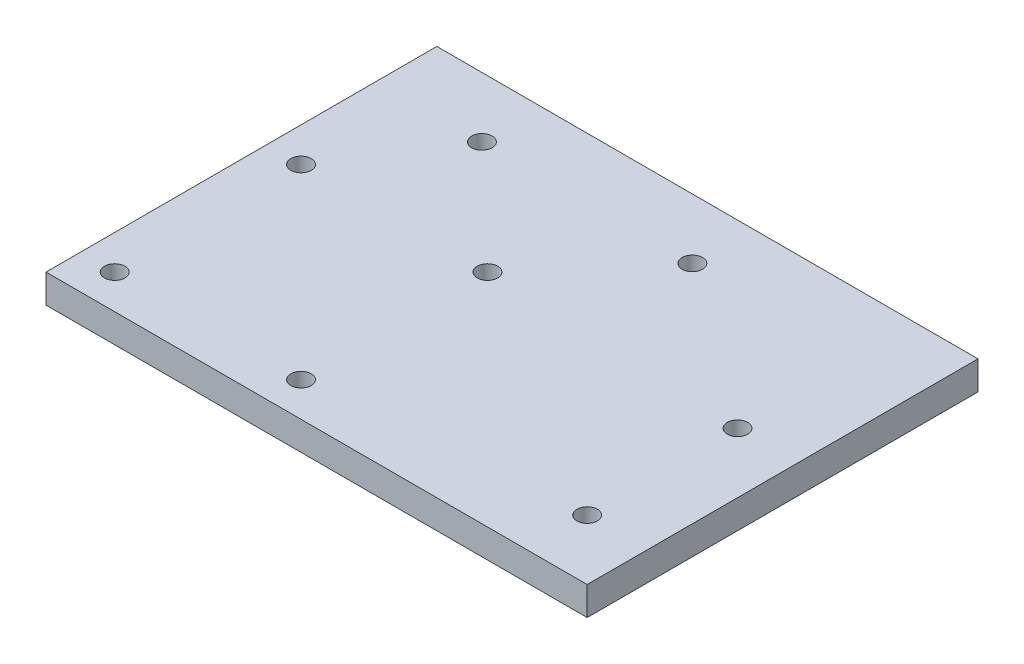
SolidWorks part; units mm, degrees
material "6061 Alloy"
ref_plane "Front Plane" through (0, 0, 0) normal (0, 0, 1) x (1, 0, 0)
ref_plane "Top Plane" through (0, 0, 0) normal (0, 1, 0) x (1, 0, 0)
ref_plane "Right Plane" through (0, 0, 0) normal (1, 0, 0) x (0, 0, -1)
sketch "Sketch1" plane through (0, 0, 0) normal (0, 1, 0) x (1, 0, 0)
  line L1 (0, 0) -> (90, 0)
  line L2 (0, 0) -> (0, 65)
  line L3 (0, 65) -> (90, 65)
  line L4 (90, 0) -> (90, 65)
  dimension "D1" = 90
  dimension "D2" = 65
extrude "Boss-Extrude1" add sketch "Sketch1" along normal blind 4.7625
sketch "Sketch3" plane through (0, 0, 0) normal (0, -1, 0) x (1, 0, 0)
  line L9 (35, -55) -> (35, -65) construction
  line L10 (90, -22.5) -> (80, -22.5) construction
  line L11 (80, -55) -> (0, -55) construction
  line L14 (80, 0) -> (80, -55) construction
  point P46 (52.5, -55)
  point P47 (17.5, -55)
  point P48 (80, -35)
  point P49 (80, -10)
  point P50 (36.709, -5.709)
  point P51 (36.709, -36.709)
  point P52 (5.709, -5.709)
  point P53 (5.709, -36.709)
hole_wizard "M3 Clearance Hole1" positions "Sketch4" profile "Sketch5" hole size "M3" standard "ANSI Metric" end condition through all
sketch "Sketch4" plane through (0, 4.7625, 0) normal (0, 1, 0) x (1, 0, 0)
  point P0 (36.709, 5.709)
  point P3 (36.709, 36.709)
  point P6 (5.709, 36.709)
  point P9 (5.709, 5.709)
  point P28 (10.1529, 5.709)
  point P29 (5.709, 5.709)
  point P31 (5.709, 36.709)
  point P33 (36.709, 36.709)
  point P35 (36.709, 5.709)
sketch "Sketch5" plane through (36.709, 4.7625, -5.709) normal (1, 0, 0) x (0, 0, 1)
  line L0 (0, 0) -> (0, 4.7625)
  line L1 (0, 4.7625) -> (1.7, 4.7625)
  line L2 (1.7, 4.7625) -> (1.7, 0)
  line L5 (1.7, 0) -> (0, 0)
  line L11 (0, -6.35) -> (0, 107.95) construction
  dimension "Thru Hole Dia." = 3.4
  dimension "Thru Hole Depth" = 4.7625
hole_wizard "M3 Clearance Hole2" positions "Sketch6" profile "Sketch7" hole size "M3" standard "ANSI Metric" end condition through all
sketch "Sketch6" plane through (0, 0, 0) normal (0, -1, 0) x (-1, 0, 0)
  point P0 (-17.5, 55)
  point P3 (-52.5, 55)
  point P6 (-80, 35)
  point P9 (-80, 10)
  point P16 (-80, 10)
  point P18 (-80, 35)
  point P20 (-52.5, 55)
  point P22 (-17.5, 55)
sketch "Sketch7" plane through (17.5, 0, -55) normal (1, 0, 0) x (0, 0, -1)
  line L0 (0, 0) -> (0, 4.7625)
  line L1 (0, 4.7625) -> (1.7, 4.7625)
  line L2 (1.7, 4.7625) -> (1.7, 0)
  line L5 (1.7, 0) -> (0, 0)
  line L11 (0, -6.35) -> (0, 107.95) construction
  dimension "Thru Hole Dia." = 3.4
  dimension "Thru Hole Depth" = 4.7625
